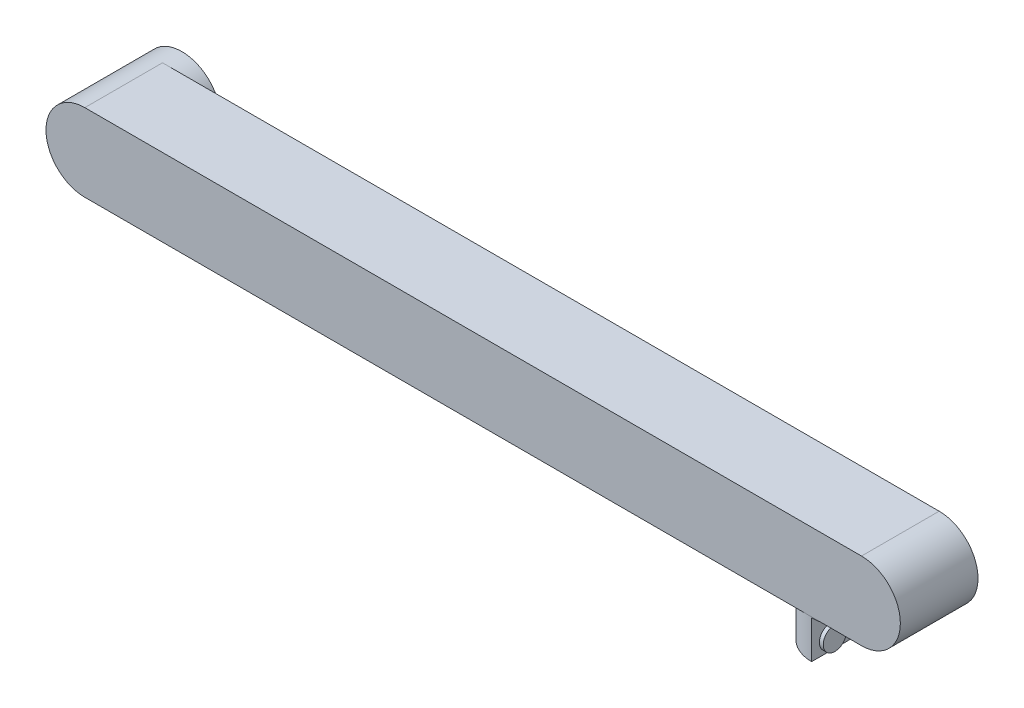
SolidWorks part; units mm, degrees
ref_plane "Front Plane" through (0, 0, 0) normal (0, 0, 1) x (1, 0, 0)
ref_plane "Top Plane" through (0, 0, 0) normal (0, 1, 0) x (1, 0, 0)
ref_plane "Right Plane" through (0, 0, 0) normal (1, 0, 0) x (0, 0, -1)
sketch "Sketch2" plane through (0, 0, 0) normal (0, 0, 1) x (1, 0, 0)
  line L0 (-70.1395, 19.2078) -> (129.8605, 19.2078)
  line L1 (129.8605, -0.7922) -> (-70.1395, -0.7922)
  arc A0 (129.8605, 19.2078) -> (139.8605, 9.2078) centre (129.8605, 9.2078) cw
  arc A1 (139.8605, 9.2078) -> (129.8605, -0.7922) centre (129.8605, 9.2078) cw
  arc A2 (-70.1395, 19.2078) -> (-80.1395, 9.2078) centre (-70.1395, 9.2078) ccw
  arc A3 (-80.1395, 9.2078) -> (-70.1395, -0.7922) centre (-70.1395, 9.2078) ccw
extrude "Boss-Extrude1" add sketch "Sketch2" along normal blind 20
sketch "Sketch4" plane through (0, -0.7922, 0) normal (0, -1, 0) x (1, 0, 0)
  circle A0 centre (117.0872, 10) radius 10
extrude "Boss-Extrude3" add sketch "Sketch4" along normal blind 10
ref_plane "Plane1" through (117, 0, 0) normal (1, 0, 0) x (0, 0, -1)
sketch "Sketch5" plane through (117, 0, 0) normal (1, 0, 0) x (0, 0, -1)
  line L1 (-22.2652, -0.9905) -> (1.6428, -0.9905)
  line L2 (-22.2652, -0.9905) -> (-22.2652, -11.2187)
  line L3 (-22.2652, -11.2187) -> (1.6428, -11.2187)
  line L4 (1.6428, -0.9905) -> (1.6428, -11.2187)
  line L5 (-22.2652, -0.9905) -> (1.6428, -11.2187) construction
  line L6 (-22.2652, -11.2187) -> (1.6428, -0.9905) construction
  point P0 (-10.3112, -6.1046)
  point P5 (1.4323, -1.0326)
  point P6 (1.4323, -11.2187)
  point P7 (1.4323, 0)
  point P8 (1.6428, -0.9905)
extrude "Cut-Extrude2" cut sketch "Sketch5" along normal blind 50
sketch "Sketch7" plane through (0, 0, 0) normal (0, 0, -1) x (-1, 0, 0)
  circle A0 centre (70.1395, 9.2078) radius 10
extrude "Boss-Extrude4" add sketch "Sketch7" along normal blind 5
sketch "Sketch11" plane through (117, 0, 0) normal (1, 0, 0) x (0, 0, -1)
  line L0 (-10, -0.9905) -> (-10, -10.7922) construction
  line L1 (-20, -0.9905) -> (0, -0.9905) construction
  line L2 (-0.0004, -10.7922) -> (-19.9996, -10.7922) construction
  line L3 (-10, -10.7922) -> (-19.9996, -10.7922) construction
  line L4 (-19.9996, -10.7922) -> (-20, -0.7922) construction
  line L5 (-20, -0.7922) -> (-10, -0.9905) construction
  line L6 (-10, -0.9905) -> (0, -0.9905) construction
  line L7 (0, -0.9905) -> (-0.0004, -10.7922) construction
  line L8 (-0.0004, -10.7922) -> (-10, -10.7922) construction
  circle A0 centre (-14.9923, -7.5147) radius 3
  circle A1 centre (-5, -7.5147) radius 3
extrude "Boss-Extrude7" add sketch "Sketch11" along normal blind 1
